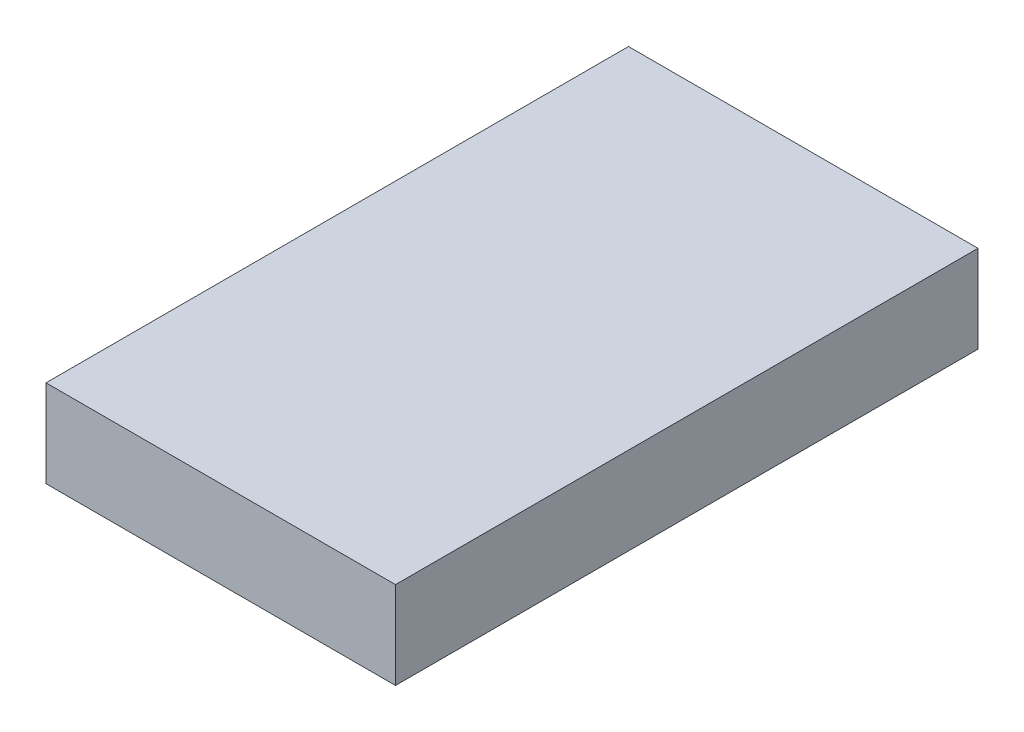
SolidWorks part; units mm, degrees
ref_plane "Front Plane" through (0, 0, 0) normal (0, 0, 1) x (1, 0, 0)
ref_plane "Top Plane" through (0, 0, 0) normal (0, 1, 0) x (1, 0, 0)
ref_plane "Right Plane" through (0, 0, 0) normal (1, 0, 0) x (0, 0, -1)
sketch "Sketch1" plane through (0, 0, 0) normal (0, 0, 1) x (1, 0, 0)
  line L1 (-30, 7.5) -> (30, 7.5)
  line L2 (-30, 7.5) -> (-30, -7.5)
  line L3 (-30, -7.5) -> (30, -7.5)
  line L4 (30, 7.5) -> (30, -7.5)
  line L5 (-30, 7.5) -> (30, -7.5) construction
  line L6 (-30, -7.5) -> (30, 7.5) construction
  point P0 (0, 0)
  dimension "D1" = 15
  dimension "D2" = 60
extrude "Boss-Extrude1" add sketch "Sketch1" along normal mid plane 100
